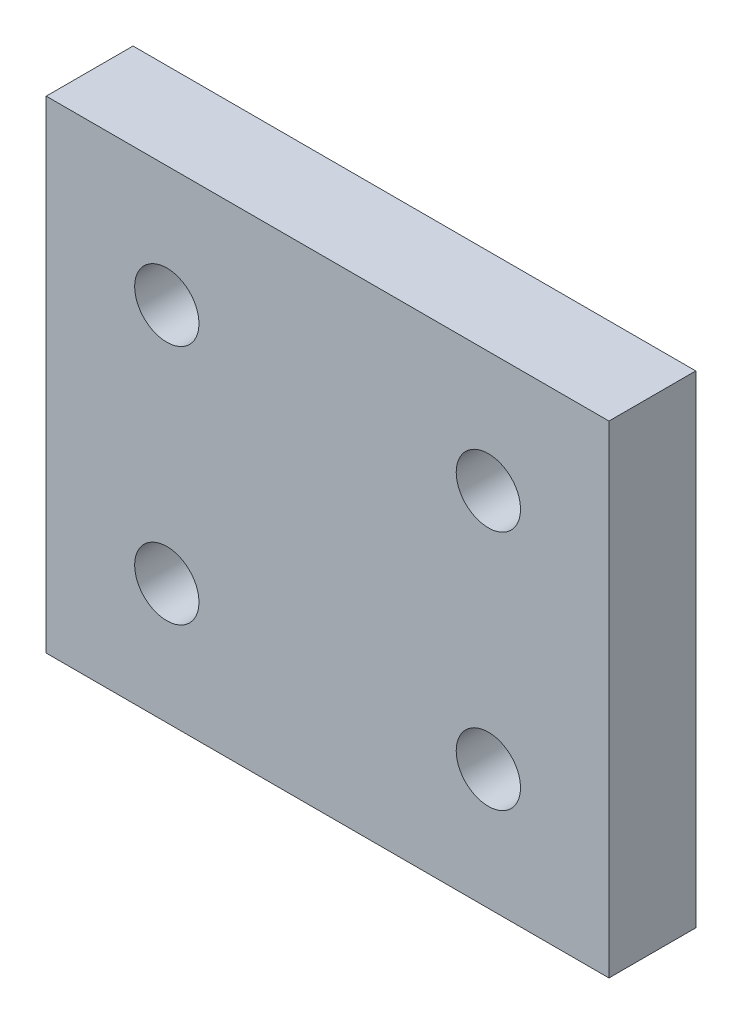
SolidWorks part; units mm, degrees
ref_plane "前视基准面" through (0, 0, 0) normal (0, 0, 1) x (1, 0, 0)
ref_plane "上视基准面" through (0, 0, 0) normal (0, 1, 0) x (1, 0, 0)
ref_plane "右视基准面" through (0, 0, 0) normal (1, 0, 0) x (0, 0, -1)
sketch "Sketch1" plane through (0, 0, 0) normal (0, 0, 1) x (1, 0, 0)
  line L1 (17.5, -30) -> (-17.5, -30)
  line L2 (17.5, -30) -> (17.5, 30)
  line L3 (17.5, 30) -> (-17.5, 30)
  line L4 (-17.5, -30) -> (-17.5, 30)
  line L5 (17.5, -30) -> (-17.5, 30) construction
  line L6 (17.5, 30) -> (-17.5, -30) construction
  point P0 (0, 0)
  dimension "D1" = 35
  dimension "D2" = 60
extrude "Boss-Extrude1" add sketch "Sketch1" along normal blind 5.4
sketch "Sketch2" plane through (0, 0, 5.4) normal (0, 0, 1) x (1, 0, 0)
  line L0 (17.5, 30) -> (-17.5, 30) construction
  line L1 (17.5, -30) -> (17.5, 30) construction
  line L2 (-17.5, -2.655) -> (17.5, -2.655)
  line L3 (-17.5, 30) -> (-17.5, -30) construction
  line L4 (-17.5, -20.2922) -> (17.5, -20.2922)
  line L5 (0, 33.1924) -> (0, -13.1081) construction
  line L6 (-17.5, 27.345) -> (17.5, 27.345)
  line L7 (-10, 19.84) -> (-10, 4.84) construction
  line L9 (-17.5, 27.345) -> (-17.5, 30)
  line L10 (-17.5, 30) -> (17.5, 30)
  line L11 (17.5, 30) -> (17.5, 27.345)
  line L12 (-17.5, -2.655) -> (-17.5, -30)
  line L13 (-17.5, -30) -> (17.5, -30)
  line L14 (17.5, -30) -> (17.5, -2.655)
  circle A0 centre (12.5, -38.32) radius 35 construction
  circle A1 centre (-10, 19.84) radius 2
  circle A2 centre (-10, 4.84) radius 2
  circle A3 centre (10, 19.84) radius 2
  circle A4 centre (10, 4.84) radius 2
  point P0 (12.5, -38.32)
  line M6 (-17.5, 30) -> (-17.5, -30)
  line M7 (-17.5, -30) -> (17.5, -30)
  line M8 (17.5, -30) -> (17.5, 30)
  line M9 (17.5, 30) -> (-17.5, 30)
  dimension "D3" = 70
  dimension "D5" = 4
  dimension "D6" = 15
  dimension "D7" = 4
  dimension "D8" = 15
  dimension "D1" = 68.32
  dimension "D2" = 35
  dimension "D4" = 10.16
  dimension "D9" = 10
  dimension "D10" = 10
extrude "Cut-Extrude1" cut sketch "Sketch2" against normal up to next and the other way through all contours L6 M6 M8 M9 | A1 | A3 | A2 | A4 | L4 L2 M6 M8 | L4 M6 M7 M8
